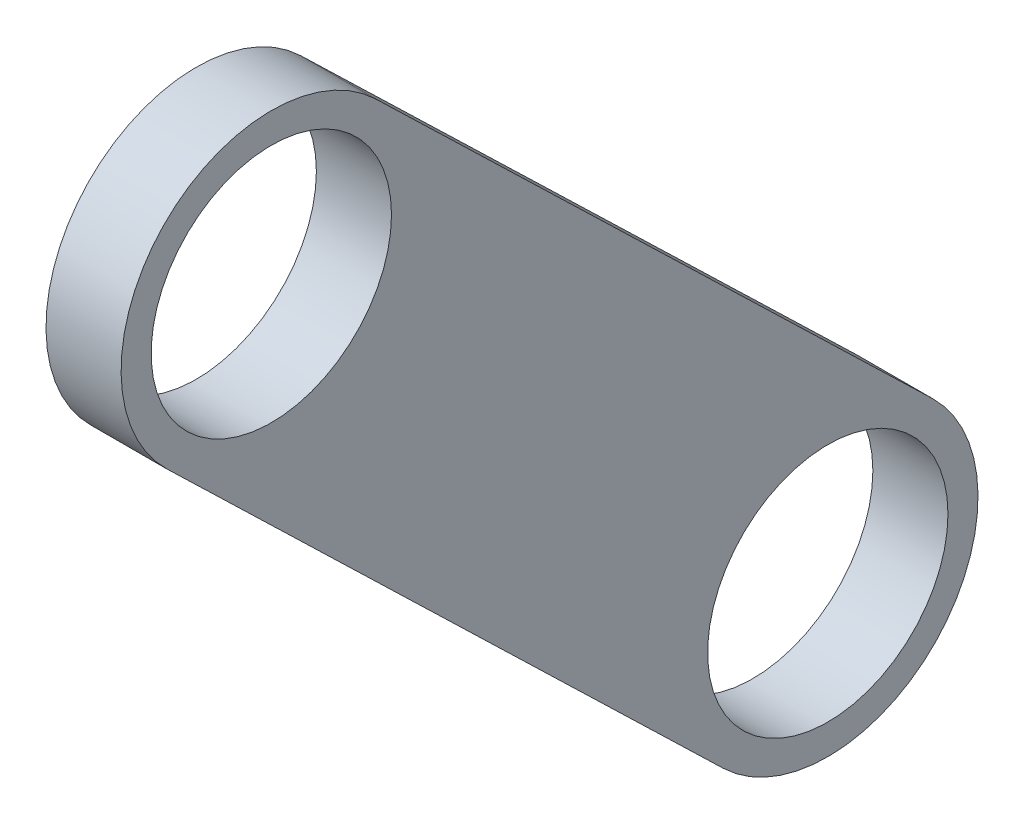
SolidWorks part; units mm, degrees
material "5052-H32"
ref_plane "Front Plane" through (0, 0, 0) normal (0, 0, 1) x (1, 0, 0)
ref_plane "Top Plane" through (0, 0, 0) normal (0, 1, 0) x (1, 0, 0)
ref_plane "Right Plane" through (0, 0, 0) normal (1, 0, 0) x (0, 0, -1)
sketch "Sketch2" plane through (0, 0, 0) normal (1, 0, 0) x (0, 0, -1)
  line L0 (43.9898, -28.5858) -> (6.9473, 7.1927)
  line L1 (-6.9473, -7.1927) -> (30.0952, -42.9713)
  arc A0 (6.9473, 7.1927) -> (-6.9473, -7.1927) centre (0, 0) ccw
  circle A1 centre (0, 0) radius 10 construction
  arc A2 (30.0952, -42.9713) -> (43.9898, -28.5858) centre (37.0425, -35.7786) ccw
  circle A3 centre (37.0425, -35.7786) radius 10 construction
  circle A4 centre (37.0425, -35.7786) radius 8
  circle A5 centre (37.0425, -35.7786) radius 8 construction
  circle A6 centre (0, 0) radius 8
  circle A7 centre (0, 0) radius 8 construction
extrude "Boss-Extrude1" add sketch "Sketch2" against normal up to vertex (9 mm away) from vertex at -4
